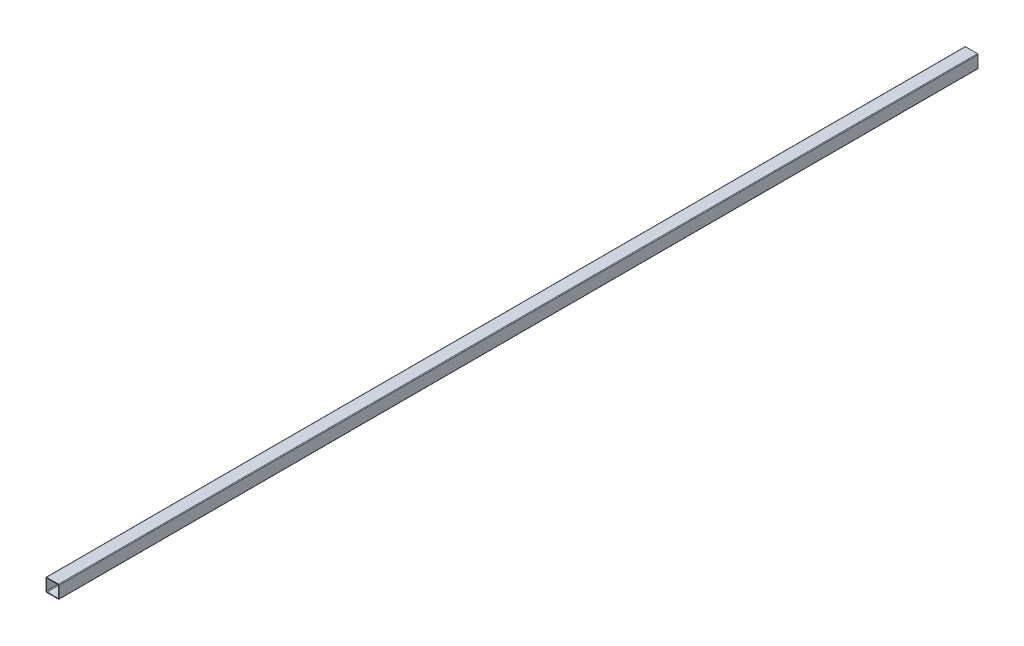
SolidWorks part; units mm, degrees
ref_plane "Спереди" through (0, 0, 0) normal (0, 0, 1) x (1, 0, 0)
ref_plane "Сверху" through (0, 0, 0) normal (0, 1, 0) x (1, 0, 0)
ref_plane "Справа" through (0, 0, 0) normal (1, 0, 0) x (0, 0, -1)
sketch "Эскиз1" plane through (0, 0, 0) normal (0, 0, 1) x (1, 0, 0)
  line L1 (18, -20) -> (-18, -20)
  line L2 (20, -18) -> (20, 18)
  line L3 (18, 20) -> (-18, 20)
  line L4 (-20, -18) -> (-20, 18)
  line L5 (20, -20) -> (-20, 20) construction
  line L6 (20, 20) -> (-20, -20) construction
  line L7 (16, -18) -> (-16, -18)
  line L8 (18, -16) -> (18, 16)
  line L9 (16, 18) -> (-16, 18)
  line L10 (-18, -16) -> (-18, 16)
  line L11 (18, -18) -> (-18, 18) construction
  line L12 (18, 18) -> (-18, -18) construction
  arc A0 (20, 18) -> (18, 20) centre (18, 18) ccw
  arc A1 (18, 16) -> (16, 18) centre (16, 16) ccw
  arc A2 (18, -20) -> (20, -18) centre (18, -18) ccw
  arc A3 (16, -18) -> (18, -16) centre (16, -16) ccw
  arc A4 (-18, -20) -> (-20, -18) centre (-18, -18) cw
  arc A5 (-16, -18) -> (-18, -16) centre (-16, -16) cw
  arc A6 (-16, 18) -> (-18, 16) centre (-16, 16) ccw
  arc A7 (-18, 20) -> (-20, 18) centre (-18, 18) ccw
  point P0 (0, 0)
  point P6 (0, 0)
  dimension "D5" = 2
  dimension "D1" = 40
  dimension "D2" = 40
  dimension "D3" = 2
  dimension "D4" = 2
extrude "Бобышка-Вытянуть1" add sketch "Эскиз1" along normal blind 2800
